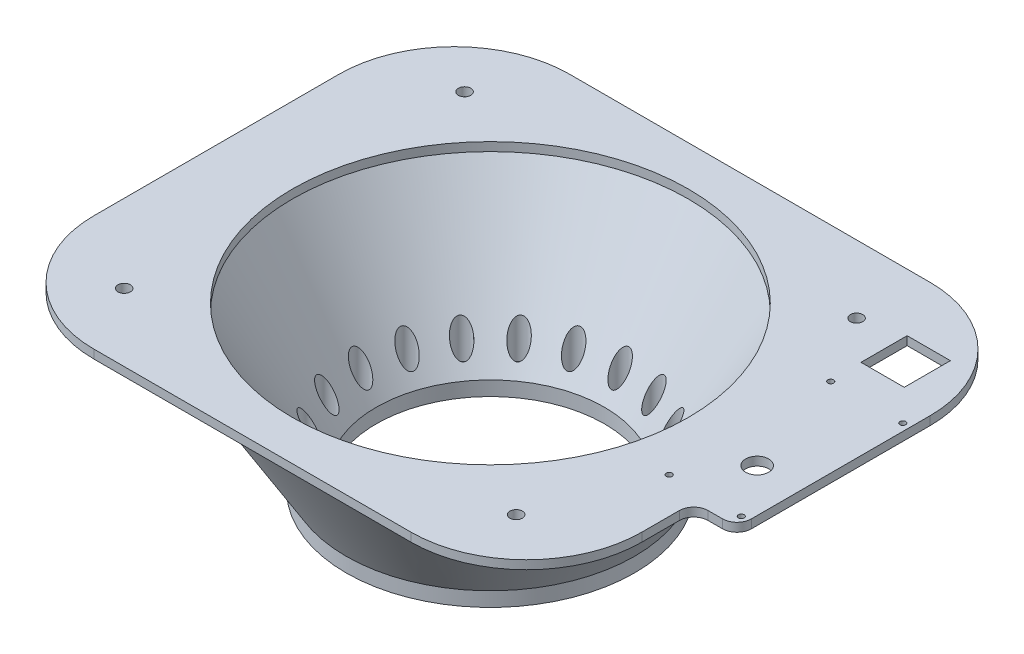
SolidWorks part; units mm, degrees
ref_plane "Front Plane" through (0, 0, 0) normal (0, 0, 1) x (1, 0, 0)
ref_plane "Top Plane" through (0, 0, 0) normal (0, 1, 0) x (1, 0, 0)
ref_plane "Right Plane" through (0, 0, 0) normal (1, 0, 0) x (0, 0, -1)
sketch "Sketch4" plane through (0, 0, 0) normal (0, 1, 0) x (1, 0, 0)
  line L0 (0, -45) -> (0, 45) construction
  line L1 (0, 0) -> (0, -45) construction
  circle A0 centre (0, 0) radius 39.565
  circle A1 centre (0, 0) radius 50
  circle A6 centre (0, -45) radius 1.75
  circle A7 centre (-13.9058, -42.7975) radius 1.75
  circle A8 centre (-26.4503, -36.4058) radius 1.75
  circle A9 centre (-36.4058, -26.4503) radius 1.75
  circle A10 centre (-42.7975, -13.9058) radius 1.75
  circle A11 centre (-45, 0) radius 1.75
  circle A12 centre (-42.7975, 13.9058) radius 1.75
  circle A13 centre (-36.4058, 26.4503) radius 1.75
  circle A14 centre (-26.4503, 36.4058) radius 1.75
  circle A15 centre (-13.9058, 42.7975) radius 1.75
  circle A16 centre (0, 45) radius 1.75
  circle A17 centre (13.9058, 42.7975) radius 1.75
  circle A18 centre (26.4503, 36.4058) radius 1.75
  circle A19 centre (36.4058, 26.4503) radius 1.75
  circle A20 centre (42.7975, 13.9058) radius 1.75
  circle A21 centre (45, 0) radius 1.75
  circle A22 centre (42.7975, -13.9058) radius 1.75
  circle A23 centre (36.4058, -26.4503) radius 1.75
  circle A24 centre (26.4503, -36.4058) radius 1.75
  circle A25 centre (13.9058, -42.7975) radius 1.75
  point P5 (0, 0)
  dimension "D1" = 79.13
  dimension "D3" = 100
  dimension "D5" = 3.5
  dimension "D2" = 90
  dimension "D7" = 45
  dimension "D6" = 20
extrude "Boss-Extrude3" add sketch "Sketch4" along normal blind 5
sketch "Sketch6" plane through (0, 0, 0) normal (1, 0, 0) x (0, 0, -1)
  line L0 (-50, 5) -> (-79.0628, 53)
  line L2 (-50, 5) -> (-39.565, 5)
  line L3 (-39.565, 5) -> (-68.6278, 53)
  line L5 (-68.6278, 53) -> (-79.0628, 53)
  dimension "D1" = 18.6278
  dimension "D2" = 48
ref_plane "Plane1" through (0, 15, 0) normal (0, 1, 0) x (1, 0, 0)
ref_axis "Axis1" through (0, 0, 0) along (0, 1, 0)
revolve "Revolve1" add sketch "Sketch6" angle 360 about axis through (0, 0, 0) along (0, 1, 0)
sketch "Sketch7" plane through (0, 53, 0) normal (0, 1, 0) x (1, 0, 0)
  line L1 (-95, 82.5) -> (95, 82.5)
  line L2 (-95, 82.5) -> (-95, -82.5)
  line L3 (-95, -82.5) -> (95, -82.5)
  line L4 (95, 82.5) -> (95, -82.5)
  line L5 (-95, 82.5) -> (95, -82.5) construction
  line L6 (-95, -82.5) -> (95, 82.5) construction
  circle A0 centre (0, 0) radius 68.6289
  circle A1 centre (-67.953, 59.0118) radius 2.15
  circle A2 centre (67.953, 59.0118) radius 2.15
  circle A3 centre (67.953, -59.0118) radius 2.15
  circle A4 centre (-67.953, -59.0118) radius 2.15
  point P4 (0, 0)
  dimension "D5" = 4.3
  dimension "D1" = 190
  dimension "D2" = 165
  dimension "D3" = 90
  dimension "D4" = 90
extrude "Boss-Extrude4" add sketch "Sketch7" along normal blind 3
fillet "Fillet1" radius 40 4 edges at (95, 54.5, -82.5) (95, 54.5, 82.5) (-95, 54.5, 82.5) (-95, 54.5, -82.5)
sketch "Sketch8" plane through (0, 0, 0) normal (0, -1, 0) x (1, 0, 0)
  line L0 (0, 0) -> (0, -45) construction
  circle A0 centre (0, -45) radius 3
  circle A1 centre (-13.9058, -42.7975) radius 3
  circle A2 centre (-26.4503, -36.4058) radius 3
  circle A3 centre (-36.4058, -26.4503) radius 3
  circle A4 centre (-42.7975, -13.9058) radius 3
  circle A5 centre (-45, 0) radius 3
  circle A6 centre (-42.7975, 13.9058) radius 3
  circle A7 centre (-36.4058, 26.4503) radius 3
  circle A8 centre (-26.4503, 36.4058) radius 3
  circle A9 centre (-13.9058, 42.7975) radius 3
  circle A10 centre (0, 45) radius 3
  circle A11 centre (13.9058, 42.7975) radius 3
  circle A12 centre (26.4503, 36.4058) radius 3
  circle A13 centre (36.4058, 26.4503) radius 3
  circle A14 centre (42.7975, 13.9058) radius 3
  circle A15 centre (45, 0) radius 3
  circle A16 centre (42.7975, -13.9058) radius 3
  circle A17 centre (36.4058, -26.4503) radius 3
  circle A18 centre (26.4503, -36.4058) radius 3
  circle A19 centre (13.9058, -42.7975) radius 3
  dimension "D1" = 20
  dimension "D3" = 6
  dimension "D2" = 45
extrude "Cut-Extrude1" cut sketch "Sketch8" against normal through all from offset 5 offset against normal yes
sketch "Sketch9" plane through (0, 56, 0) normal (0, 1, 0) x (1, 0, 0)
  line L0 (-55, -82.5) -> (55, -82.5) construction
  line L1 (74, -1.5) -> (80, -1.5)
  line L2 (74, -1.5) -> (74, -11.5)
  line L3 (74, -11.5) -> (80, -11.5)
  line L4 (80, -1.5) -> (80, -11.5)
  line L5 (95, -42.5) -> (95, 42.5) construction
  dimension "D1" = 6
  dimension "D2" = 10
  dimension "D3" = 71
  dimension "D4" = 15
extrude "Boss-Extrude5" [suppressed] add sketch "Sketch9" along normal blind 5
sketch "Sketch10" [suppressed] plane through (0, 0, 11.5) normal (0, 0, 1) x (1, 0, 0)
  line L0 (77, 58.5) -> (77, 61) construction
  line L1 (74, 61) -> (80, 61) construction
  line L2 (95, 56) -> (55, 56) construction
  circle A0 centre (77, 58.5) radius 1.75
  dimension "D1" = 3.5
  dimension "D2" = 2.5
extrude "Cut-Extrude2" [suppressed] cut sketch "Sketch10" against normal up to next
sketch "Sketch11" plane through (0, 56, 0) normal (0, 1, 0) x (1, 0, 0)
  line L0 (-55, -82.5) -> (55, -82.5) construction
  line L1 (55, 82.5) -> (110, 82.5)
  line L2 (55, 82.5) -> (55, 68.6019)
  line L3 (78.9066, -24.5) -> (110, -24.5)
  line L4 (110, 82.5) -> (110, -24.5)
  line L6 (95, -42.5) -> (95, 42.5) construction
  line L7 (55, 68.6019) -> (78.9066, 68.6019)
  line L8 (78.9066, 68.6019) -> (78.9066, -24.5)
  arc A0 (95, 42.5) -> (55, 82.5) centre (55, 42.5) ccw construction
  dimension "D2" = 58
  dimension "D4" = 15
extrude "Boss-Extrude7" add sketch "Sketch11" against normal up to surface (3 mm away) up to face at (0, 53, -79.0628)
sketch "Sketch12" plane through (0, 56, 0) normal (0, 1, 0) x (1, 0, 0)
  line L2 (-55, -82.5) -> (55, -82.5) construction
  line L3 (95, -42.5) -> (95, -24.5) construction
  circle A0 centre (95, -2.5) radius 4
  dimension "D1" = 8
  dimension "D2" = 0
  dimension "D3" = 80
extrude "Cut-Extrude3" cut sketch "Sketch12" against normal through all
fillet "Fillet2" radius 40 1 edges at (110, 54.5, -82.5)
fillet "Fillet3" radius 5 2 edges at (110, 54.5, 24.5) (95, 54.5, 24.5)
sketch "Sketch15" plane through (0, 56, 0) normal (0, 1, 0) x (1, 0, 0)
  circle A0 centre (107.5, -20.5) radius 1 construction
  circle A1 centre (107.5, 35.5) radius 1 construction
  circle A2 centre (107.5, -20.5) radius 1
  circle A3 centre (107.5, 35.5) radius 1
  circle A4 centre (82.5, -20.5) radius 1 construction
  circle A5 centre (82.5, 35.5) radius 1 construction
  circle A6 centre (82.5, -20.5) radius 1
  circle A7 centre (82.5, 35.5) radius 1
extrude "Cut-Extrude5" cut sketch "Sketch15" against normal up to next
sketch "Sketch13" plane through (0, 56, 0) normal (0, 1, 0) x (1, 0, 0)
  line L0 (70, 82.5) -> (-55, 82.5) construction
  line L1 (82, 62.5) -> (97, 62.5)
  line L2 (82, 62.5) -> (82, 46.5)
  line L3 (82, 46.5) -> (97, 46.5)
  line L4 (97, 62.5) -> (97, 46.5)
  line L5 (110, -19.5) -> (110, 42.5) construction
  dimension "D1" = 15
  dimension "D2" = 20
  dimension "D3" = 13
  dimension "D4" = 16
extrude "Cut-Extrude4" cut sketch "Sketch13" against normal through all
